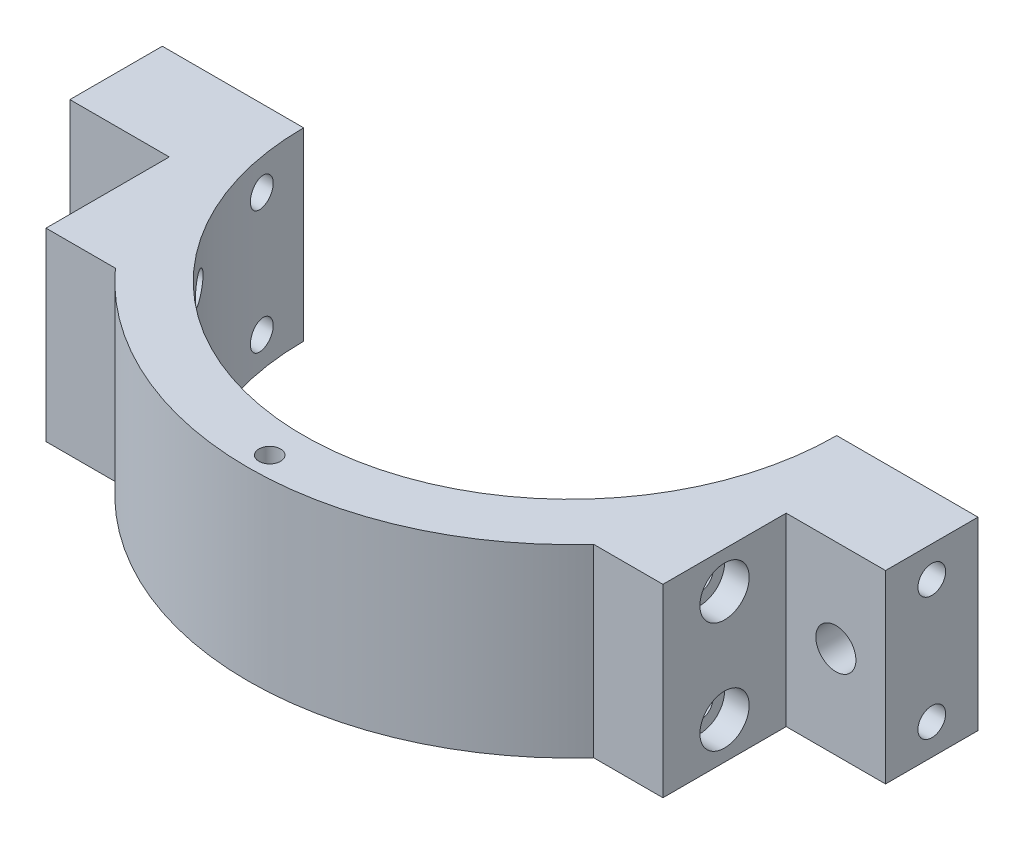
SolidWorks part; units mm, degrees
ref_plane "Front Plane" through (0, 0, 0) normal (0, 0, 1) x (1, 0, 0)
ref_plane "Top Plane" through (0, 0, 0) normal (0, 1, 0) x (1, 0, 0)
ref_plane "Right Plane" through (0, 0, 0) normal (1, 0, 0) x (0, 0, -1)
sketch "Sketch1" plane through (0, 0, 0) normal (0, 1, 0) x (1, 0, 0)
  line L0 (-43.25, 0) -> (-66.175, 0)
  line L4 (66.175, 0) -> (43.25, 0)
  line L5 (0, 0) -> (0, -67.037) construction
  line L6 (-66.175, 0) -> (-66.175, -15)
  line L7 (-66.175, -15) -> (-50.0506, -15)
  line L8 (66.175, -15) -> (50.0506, -15)
  line L9 (66.175, 0) -> (66.175, -15)
  circle A0 centre (0, 0) radius 43.25 construction
  arc A1 (-43.25, 0) -> (43.25, 0) centre (0, 0) ccw
  arc A2 (-50.0506, -15) -> (50.0506, -15) centre (0, 0) ccw
  dimension "D1" = 86.5
  dimension "D2" = 52.25
  dimension "D3" = 15
  dimension "D4" = 132.35
extrude "Boss-Extrude1" add sketch "Sketch1" along normal mid plane 30
sketch "Sketch2" plane through (0, 0, 15) normal (0, 0, 1) x (1, 0, 0)
  line L0 (-58.1128, -15) -> (-58.1128, 15) construction
  line L1 (-66.175, -15) -> (-50.0506, -15) construction
  line L2 (-66.175, 15) -> (-50.0506, 15) construction
  line L3 (0, 0) -> (0, 15) construction
  line L4 (50.0506, 15) -> (-50.0506, 15) construction
  circle A0 centre (-58.1128, 0) radius 3.25
  circle A1 centre (58.1128, 0) radius 3.25
  dimension "D1" = 6.5
extrude "Cut-Extrude1" cut sketch "Sketch2" against normal through all
sketch "Sketch3" plane through (-66.175, 0, 0) normal (-1, 0, 0) x (0, 0, 1)
  line L0 (7.5, 15) -> (7.5, -15) construction
  line L1 (0, 15) -> (15, 15) construction
  line L2 (0, -15) -> (15, -15) construction
  line L3 (15, 0) -> (0, 0) construction
  line L4 (15, 15) -> (15, -15) construction
  circle A0 centre (7.5, -10) radius 2.25
  circle A1 centre (7.5, 10) radius 2.25
  dimension "D1" = 20
  dimension "D2" = 4.5
extrude "Cut-Extrude2" cut sketch "Sketch3" against normal through all
sketch "Sketch4" plane through (0, 15, 0) normal (0, 1, 0) x (1, 0, 0)
  circle A0 centre (0, -48.75) radius 1.75
  arc A1 (-43.25, 0) -> (43.25, 0) centre (0, 0) ccw construction
  arc A2 (-50.0506, -15) -> (50.0506, -15) centre (0, 0) ccw construction
  point P2 (0, -43.25)
  point P9 (0, -52.25)
  dimension "D1" = 3.5
extrude "Cut-Extrude3" cut sketch "Sketch4" against normal through all both and the other way through all contours A0
sketch "Sketch5" plane through (0, 15, 0) normal (0, 1, 0) x (1, 0, 0)
  line L0 (-50.0506, -15) -> (-50.0506, -35)
  line L1 (-50.0506, -35) -> (-38.7951, -35)
  arc A0 (-50.0506, -15) -> (50.0506, -15) centre (0, 0) ccw construction
  arc A1 (-50.0506, -15) -> (-38.7951, -35) centre (0, 0) ccw
  dimension "D1" = 20
extrude "Boss-Extrude2" add sketch "Sketch5" against normal up to surface (30 mm away) up to face at (0, -15, 50.5)
ref_plane "Plane1" through (0, 0, 0) normal (-1, 0, 0) x (0, 0, 1)
mirror "Mirror1" about plane through (0, 0, 0) normal (-1, 0, 0) of "Boss-Extrude2"
hole_wizard "CBORE for M4 SHCS1" positions "Sketch9" profile "Sketch10" counterbore size "M4" standard "ANSI Metric"
sketch "Sketch9" plane through (50.0506, 54.222, 632.5589) normal (1, 0, 0) x (0, -0.938, -0.3467)
  line L0 (253.0708, 554.1913) -> (269.9543, 547.9503) construction
  line L2 (261.5125, 551.0708) -> (258.0453, 541.6911) construction
  circle A0 centre (253.0708, 554.1913) radius 2.25
  circle A1 centre (269.9543, 547.9503) radius 2.25
  point P0 (253.0708, 554.1913)
  point P2 (269.9543, 547.9503)
sketch "Sketch10" plane through (50.0506, 9, 25) normal (0, 1, 0) x (0, 0, -1)
  line L0 (0, 0) -> (0, 101.393)
  line L1 (0, 101.393) -> (2.15, 100.1012)
  line L2 (2.15, 100.1012) -> (2.15, 4)
  line L3 (2.15, 4) -> (4, 4)
  line L4 (4, 4) -> (4, 0)
  line L5 (4, 0) -> (0, 0)
  line L6 (0, 101.393) -> (-2.15, 100.1012) construction
  line L7 (0, -6.35) -> (0, 107.95) construction
  dimension "Hole Dia." = 4.3
  dimension "Hole Depth" = 100.1012
  dimension "C'Bore Dia." = 8
  dimension "C'Bore Depth" = 4
  dimension "Drill Angle" = 118
